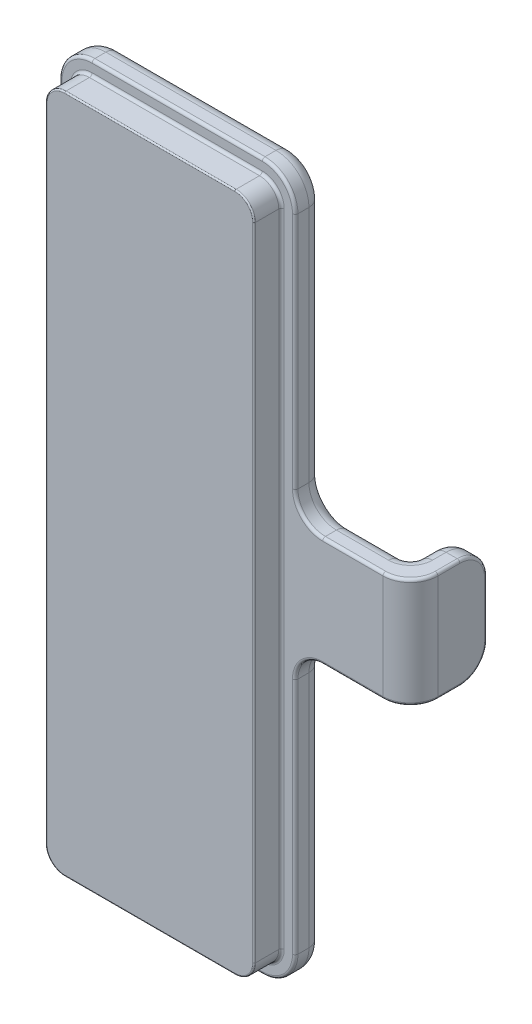
SolidWorks part; units mm, degrees
ref_plane "Front Plane" through (0, 0, 0) normal (0, 0, 1) x (1, 0, 0)
ref_plane "Top Plane" through (0, 0, 0) normal (0, 1, 0) x (1, 0, 0)
ref_plane "Right Plane" through (0, 0, 0) normal (1, 0, 0) x (0, 0, -1)
sketch "Sketch1" plane through (0, 0, 0) normal (0, 0, 1) x (1, 0, 0)
  line L0 (21.2752, -27.0671) -> (21.2752, -49.8367) construction
  line L1 (21.2752, -49.8367) -> (26.8752, -49.8367) construction
  line L2 (26.8752, -49.8367) -> (26.8752, -27.0671) construction
  line L3 (26.8752, -27.0671) -> (21.2752, -27.0671) construction
  line L4 (27.8752, -26.0671) -> (20.2752, -26.0671)
  line L5 (20.2752, -26.0671) -> (20.2752, -50.8367)
  line L6 (20.2752, -50.8367) -> (27.8752, -50.8367)
  line L7 (27.8752, -50.8367) -> (27.8752, -26.0671)
  line L8 (21.1752, -26.9671) -> (21.1752, -49.9367) construction
  line L9 (21.1752, -49.9367) -> (26.9752, -49.9367) construction
  line L10 (26.9752, -49.9367) -> (26.9752, -26.9671) construction
  line L11 (26.9752, -26.9671) -> (21.1752, -26.9671) construction
  dimension "D1" = 0.1
  dimension "D2" = 1
extrude "Boss-Extrude1" add sketch "Sketch1" against normal blind 2
sketch "Sketch2" plane through (0, 0, -2) normal (0, 0, -1) x (-1, 0, 0)
  line L1 (-20.7752, -50.3367) -> (-20.7752, -26.5671) construction
  line L2 (-20.7752, -26.5671) -> (-27.3752, -26.5671) construction
  line L3 (-27.3752, -26.5671) -> (-27.3752, -50.3367) construction
  line L4 (-27.8752, -26.0671) -> (-27.8752, -50.8367)
  line L5 (-27.8752, -26.0671) -> (-27.8752, -50.8367) construction
  line L6 (-27.8752, -50.8367) -> (-20.2752, -50.8367)
  line L7 (-27.8752, -50.8367) -> (-20.2752, -50.8367) construction
  line L12 (-27.3752, -50.3367) -> (-20.7752, -50.3367) construction
  line L16 (-20.2752, -50.8367) -> (-20.2752, -26.0671)
  line L17 (-20.2752, -50.8367) -> (-20.2752, -26.0671) construction
  line L18 (-20.2752, -26.0671) -> (-27.8752, -26.0671)
  line L19 (-20.2752, -26.0671) -> (-27.8752, -26.0671) construction
  line L20 (-28.3752, -25.5671) -> (-28.3752, -51.3367)
  line L21 (-28.3752, -51.3367) -> (-19.7752, -51.3367)
  line L22 (-19.7752, -51.3367) -> (-19.7752, -25.5671)
  line L23 (-19.7752, -25.5671) -> (-28.3752, -25.5671)
  dimension "D1" = 0
  dimension "D2" = 1
extrude "Boss-Extrude2" add sketch "Sketch2" against normal blind 1
sketch "Sketch3" plane through (28.3752, -22.9614, 0) normal (-1, 0, 0) x (0, 0, -1)
  line L9 (2, 17.4905) -> (1, 17.4905)
  line L10 (2, 13.4905) -> (1, 13.4905)
  line L11 (2, 17.4905) -> (2, 13.4905)
  line L12 (1, 17.4905) -> (1, 13.4905)
extrude "Boss-Extrude3" add sketch "Sketch3" against normal blind 4.2
sketch "Sketch4" plane through (65.1505, 0, -2) normal (0, 0, 1) x (1, 0, 0)
  line L5 (-33.5752, -40.4519) -> (-32.5752, -40.4519)
  line L6 (-33.5752, -40.4519) -> (-33.5752, -36.4519)
  line L7 (-32.5752, -40.4519) -> (-32.5752, -36.4519)
  line L8 (-32.5752, -36.4519) -> (-33.5752, -36.4519)
extrude "Boss-Extrude4" add sketch "Sketch4" against normal blind 1.8
fillet "Fillet1" radius 1 1 edges at (32.5752, -38.4519, -1)
fillet "Fillet2" radius 0.3 1 edges at (31.5752, -38.4519, -2)
fillet "Fillet3" radius 1 4 edges at (28.3752, -36.4519, -1.5) (28.3752, -40.4519, -1.5) (32.0752, -36.4519, -3.8) (32.0752, -40.4519, -3.8)
fillet "Fillet4" radius 1.2 4 edges at (19.7752, -51.3367, -1.5) (19.7752, -25.5671, -1.5) (28.3752, -25.5671, -1.5) (28.3752, -51.3367, -1.5)
fillet "Fillet5" radius 0.7 4 edges at (27.8752, -26.0671, -0.5) (20.2752, -26.0671, -0.5) (20.2752, -50.8367, -0.5) (27.8752, -50.8367, -0.5)
fillet "Fillet6" radius 0.1 28 edges at (28.0238, -25.9186, -1) (24.0752, -25.5671, -1) (20.1267, -25.9186, -1) (19.7752, -38.4519, -1) (20.1267, -50.9852, -1) (24.0752, -51.3367, -1) (28.0238, -50.9852, -1) (28.3752, -45.7943, -1) (28.6681, -40.7448, -1) (30.4752, -40.4519, -1) (32.2824, -40.4519, -1.2929) (32.5752, -40.4519, -2.4) (32.5752, -40.159, -3.5071) (32.5752, -38.4519, -3.8) (32.5752, -36.7448, -3.5071) (32.5752, -36.4519, -2.4) (32.2824, -36.4519, -1.2929) (30.4752, -36.4519, -1) (28.6681, -36.159, -1) (27.6702, -50.6316, -1) (24.0752, -50.8367, -1) (20.4803, -50.6316, -1) (20.2752, -38.4519, -1) (20.4803, -26.2721, -1) (24.0752, -26.0671, -1) (27.6702, -26.2721, -1) (28.3752, -31.1095, -1) (27.8752, -38.4519, -1)
fillet "Fillet7" radius 0.05 8 edges at (24.0752, -50.8367, 0) (20.2752, -38.4519, 0) (24.0752, -26.0671, 0) (27.8752, -38.4519, 0) (27.6702, -50.6316, 0) (20.4803, -50.6316, 0) (20.4803, -26.2721, 0) (27.6702, -26.2721, 0)
fillet "Fillet8" radius 0.5 20 edges at (20.1267, -50.9852, -2) (24.0752, -51.3367, -2) (28.0238, -50.9852, -2) (28.3752, -45.7943, -2) (28.6681, -40.7448, -2) (30.3252, -40.4519, -2) (31.4874, -40.4519, -2.0879) (31.5752, -40.4519, -2.55) (31.5752, -40.159, -3.5071) (31.5752, -38.4519, -3.8) (31.5752, -36.7448, -3.5071) (31.5752, -36.4519, -2.55) (31.4874, -36.4519, -2.0879) (30.3252, -36.4519, -2) (28.6681, -36.159, -2) (28.3752, -31.1095, -2) (28.0238, -25.9186, -2) (24.0752, -25.5671, -2) (20.1267, -25.9186, -2) (19.7752, -38.4519, -2)
